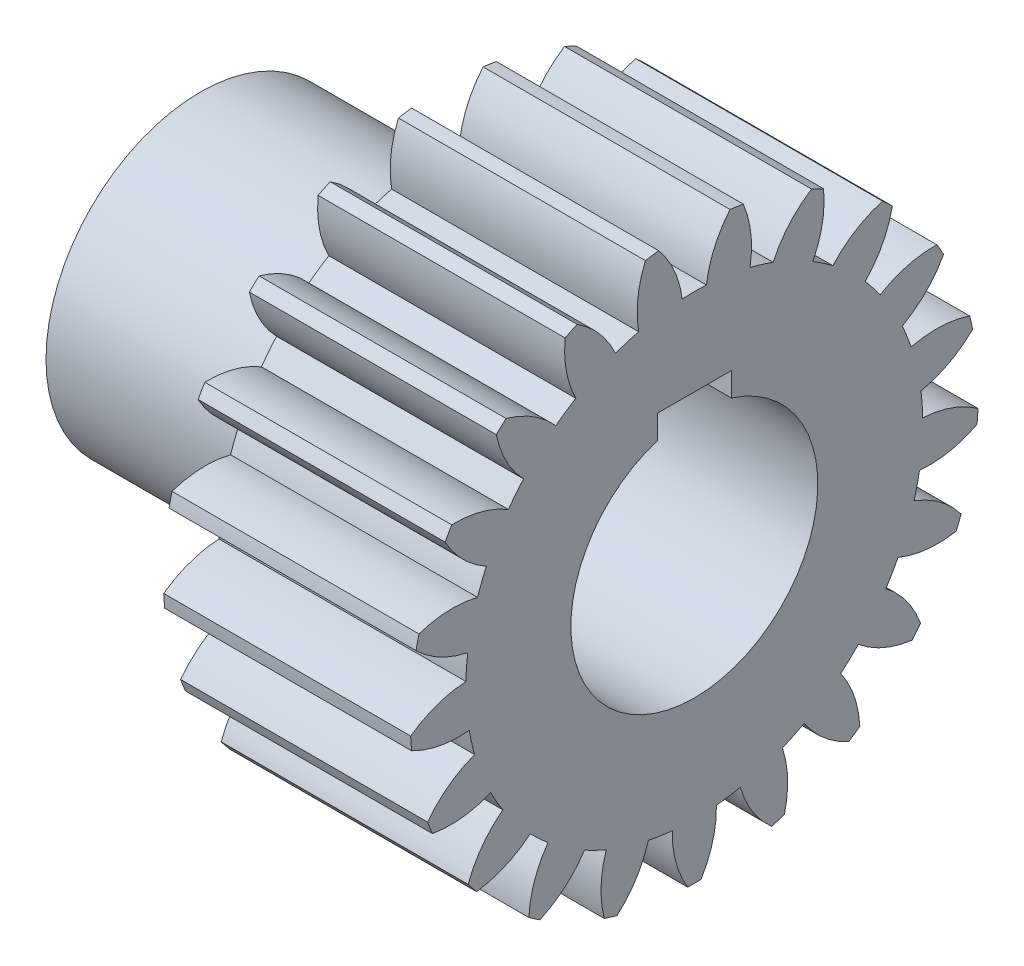
SolidWorks part; units mm, degrees
ref_plane "Plane1" through (0, 0, 0) normal (0, 0, 1) x (1, 0, 0)
ref_plane "Plane2" through (0, 0, 0) normal (0, 1, 0) x (1, 0, 0)
ref_plane "Plane3" through (0, 0, 0) normal (1, 0, 0) x (0, 0, -1)
sketch "HoldingSke" plane through (0, 0, 0) normal (0, 1, 0) x (1, 0, 0)
  line L0 (0, 0) -> (0.1556, -0.0597)
  line L1 (-15, 0) -> (100, 0) construction
  line L2 (0, 0) -> (-2.1039, 2.3779)
  line L3 (0, 0) -> (-11.863, 4.5341)
  line L4 (0, 0) -> (8.0624, 3.0949)
  line L5 (0, 0) -> (-112.4343, -41.9347)
  line L6 (0, 0) -> (-49.7378, -33.5582)
  line L7 (-2.1039, 2.3779) -> (23.726, 119.565)
  line L8 (-76.2, 54.61) -> (-71.8, 54.61)
  line L9 (-71.009, 38.7566) -> (-53.1078, 45.2721)
  line L10 (-76.2, 71.12) -> (104.1128, 71.12)
  line L11 (0, 0) -> (-60, 0)
  line L12 (-76.2, 101.6) -> (-75.993, 101.6)
  line L13 (24.9733, 27.94) -> (52.9518, 28.4284)
  line L14 (24.9733, 27.94) -> (24.9743, 27.94)
  line L15 (24.9733, 27.94) -> (100.4006, 29.5858)
  line L16 (-63.627, -6) -> (-12.827, -6)
  circle A0 centre (0, 0) radius 30
  circle A1 centre (0, 0) radius 37.5
  circle A2 centre (0, 0) radius 37.5
  circle A3 centre (0, 0) radius 30
  dimension "Num_teeth" = 21
  dimension "Pitch" = 0.1667
  dimension "Overall_len" = 120
  dimension "Show_teeth" = 21
  dimension "Thickness" = 60
  dimension "OAL" = 120.0001
  dimension "Ap" = 20
  dimension "H" = 19.05
  dimension "Pitch_radius" = 180.3128
  dimension "Width" = 60
  dimension "Backlash" = 0.207
  dimension "Addendum_fac" = 1
  dimension "Dedendum_fac" = 1.25
  dimension "Clearance_fac" = 0.25
  dimension "Dedendum_add" = 0.001
  dimension "Module" = 6
sketch "BasProSke" plane through (0, 0, 0) normal (0, 1, 0) x (1, 0, 0)
  line L0 (-10, 0) -> (60, 0) construction
  line L1 (0, 0) -> (0, 69)
  line L2 (0, 0) -> (60, 0)
  line L3 (60, 0) -> (60, 69)
  line L4 (60, 69) -> (0, 69)
  dimension "Thickness" = 60
  dimension "Diameter" = 138
revolve "Base-Revolve" add sketch "BasProSke" angle 360 about L0
sketch "TooCutSke" plane through (0, 0, 0) normal (1, 0, 0) x (0, 0, -1)
  line L1 (0, 0) -> (0, 107) construction
  line L2 (0, 0) -> (-5.0701, 62.7957) construction
  line L3 (0, 0) -> (-18.7346, 124.2959) construction
  line L4 (-5.0701, 62.7957) -> (-9.3673, 62.148) construction
  arc A0 (2.9399, 55.4211) -> (-2.9399, 55.4211) centre (0, 0) ccw
  arc A1 (8.6963, 68.4754) -> (-8.6963, 68.4754) centre (0, 0) ccw
  circle A2 centre (0, 0) radius 63 construction
  circle A3 centre (0, 0) radius 59.2006 construction
  arc A4 (-2.9399, 55.4211) -> (-8.6963, 68.4754) centre (-27.9327, 52.1965) ccw
  arc A5 (8.6963, 68.4754) -> (2.9399, 55.4211) centre (27.9327, 52.1965) ccw
  dimension "Root_dia" = 110.998
  dimension "Overcut_dia" = 138.0508
  dimension "Pitch_dia" = 126
  dimension "Base_dia" = 118.4013
  dimension "Flank_rad" = 25.2
  dimension "Half_ang" = 8.571
  dimension "Half_CT" = 4.3457
extrude "ToothCut" cut sketch "TooCutSke" along normal through all
fillet "Breaks" [suppressed] radius 0.12
fillet "RootFillets" [suppressed] radius 1.501
pattern_circular "TeethCuts" count 21 every 17.143 about axis through (-10, 0, 0) along (1, 0, 0) of "ToothCut", "RootFillets", "Breaks"
sketch "HubNeaOneSke" plane through (0, 0, 0) normal (-1, 0, 0) x (0, 0, 1)
  circle A0 centre (0, 0) radius 37.5
extrude "HubNearOne" add sketch "HubNeaOneSke" along normal blind 60.0001
sketch "HubNeaBotSke" plane through (0, 0, 0) normal (-1, 0, 0) x (0, 0, 1)
  circle A0 centre (0, 0) radius 37.5
extrude "HubNearBoth" [suppressed] add sketch "HubNeaBotSke" along normal blind 30
ref_plane "FarPln" through (60, 0, 0) normal (1, 0, 0) x (0, 0, -1)
sketch "HubFarSke" plane through (60, 0, 0) normal (1, 0, 0) x (0, 0, -1)
  circle A0 centre (0, 0) radius 37.5
extrude "HubFar" [suppressed] add sketch "HubFarSke" along normal blind 30
sketch "BorSke" plane through (0, 0, 0) normal (1, 0, 0) x (0, 0, -1)
  circle A0 centre (0, 0) radius 30
extrude "Bore" cut sketch "BorSke" along normal mid plane 240.0001
sketch "KeySke" plane through (0, 0, 0) normal (1, 0, 0) x (0, 0, -1)
  line L0 (-9, 0) -> (-9, 34.4)
  line L1 (-9, 34.4) -> (9, 34.4)
  line L2 (9, 34.4) -> (9, 0)
  line L3 (0, 0) -> (0, 34) construction
  line L4 (-9, 0) -> (9, 0)
extrude "Keyway" cut sketch "KeySke" along normal mid plane 240.0001
pattern_circular "Keyway2" [suppressed] count 2 every 90 about axis through (-10, 0, 0) along (1, 0, 0)
equation "' \"Module@HoldingSke\" = 6.35"
equation "' \"Num_teeth@HoldingSke\" = 12"
equation "' \"Ap@HoldingSke\" =  20"
equation "' \"Ap@HoldingSke\" = 20"
equation "' \"Width@HoldingSke\" = 0.5 * 25.4"
equation "' \"Hub_dia@HoldingSke\"= 1 * 25.4"
equation "' \"Hub_dia@HoldingSke\" = 1 * 25.4"
equation "' \"Overall_len@HoldingSke\" = 1.0 * 25.4"
equation "' \"Bore@HoldingSke\" = 0.75 * 25.4"
equation "' \"T_dim@HoldingSke\" = 0.1 * 25.4"
equation "' \"Width@KeySke\" = 0.25 * 25.4"
equation "' \"Show_teeth@HoldingSke\" = 13"
equation "' \"Backlash@HoldingSke\" = 0.009 * 25.4"
equation "' \"Addendum_fac@HoldingSke\" = 1.0"
equation "' \"Dedendum_fac@HoldingSke\" = 1.25"
equation "' \"Dedendum_add@HoldingSke\" = 0.00005 * 25.4"
equation "' \"Clearance_fac@HoldingSke\" = 0.25"
equation "\"Pitch@HoldingSke\" = 1 / \"Module@HoldingSke\""
equation "\"Overcut_dia@TooCutSke\" = (\"Num_teeth@HoldingSke\" + 2 * \"Addendum_fac@HoldingSke\") / \"Pitch@HoldingSke\" + 0.002 * 25.4"
equation "\"Pitch_dia@TooCutSke\" = \"Num_teeth@HoldingSke\" / \"Pitch@HoldingSke\""
equation "\"Base_dia@TooCutSke\" = \"Num_teeth@HoldingSke\" / \"Pitch@HoldingSke\" * cos((\"Ap@HoldingSke\"  * 3.14159265 / 180))"
equation "\"Root_dia@TooCutSke\" = (\"Num_teeth@HoldingSke\" + 2) / \"Pitch@HoldingSke\" - 2 * (\"Addendum_fac@HoldingSke\" + \"Dedendum_fac@HoldingSke\") / \"Pitch@HoldingSke\" - \"Dedendum_add@HoldingSke\" * 2"
equation "\"Half_ang@TooCutSke\" = 180 / \"Num_teeth@HoldingSke\""
equation "\"Half_CT@TooCutSke\" = \"Num_teeth@HoldingSke\" / \"Pitch@HoldingSke\" * sin((3.14159265 / 2 / \"Num_teeth@HoldingSke\")) / 2 - 7 * \"Backlash@HoldingSke\" / 4"
equation "\"Flank_rad@TooCutSke\" = \"Num_teeth@HoldingSke\" / \"Pitch@HoldingSke\" / 5"
equation "\"Radius@RootFillets\" = \"Clearance_fac@HoldingSke\" / \"Pitch@HoldingSke\" + \"Dedendum_add@HoldingSke\""
equation "\"Break_rad@Breaks\" = 0.02 / \"Pitch@HoldingSke\""
equation "\"Thickness@HoldingSke\" = \"Width@HoldingSke\""
equation "\"OAL@HoldingSke\" = \"Thickness@HoldingSke\""
equation "\"MHD@HoldingSke\" = (\"Num_teeth@HoldingSke\" + 2) / \"Pitch@HoldingSke\" - 2 * (\"Addendum_fac@HoldingSke\" + \"Dedendum_fac@HoldingSke\")  / \"Pitch@HoldingSke\" - \"Dedendum_add@HoldingSke\" * 2"
equation "\"MBD@HoldingSke\" = (\"Num_teeth@HoldingSke\" + 2) / \"Pitch@HoldingSke\" - 2 * (\"Addendum_fac@HoldingSke\" + \"Dedendum_fac@HoldingSke\")  / \"Pitch@HoldingSke\" - \"Dedendum_add@HoldingSke\" * 2 - 0.002 * 25.4"
equation "\"MHD@HoldingSke\" = ((sgn( \"MHD@HoldingSke\" - \"Hub_dia@HoldingSke\" )-1)*( \"MHD@HoldingSke\" - \"Hub_dia@HoldingSke\" ))/-2+ \"Hub_dia@HoldingSke\""
equation "\"MBD@HoldingSke\" = ((sgn( \"MBD@HoldingSke\" - \"Bore@HoldingSke\" )-1)*( \"MBD@HoldingSke\" - \"Bore@HoldingSke\" ))/-2+ \"Bore@HoldingSke\""
equation "\"OAL@HoldingSke\" = ((sgn( \"OAL@HoldingSke\" - \"Overall_len@HoldingSke\" )+1)*( \"OAL@HoldingSke\" - \"Overall_len@HoldingSke\" ))/2 + \"Overall_len@HoldingSke\" + 0.000002 * 25.4"
equation "\"Num_teeth@TeethCuts\" = int( \"Show_teeth@HoldingSke\" ) + 1"
equation "\"Num_teeth@TeethCuts\" = ((sgn( \"Num_teeth@TeethCuts\" - \"Num_teeth@HoldingSke\" )-1)*( \"Num_teeth@TeethCuts\" - \"Num_teeth@HoldingSke\" ))/-2+ \"Num_teeth@HoldingSke\""
equation "\"Num_teeth@TeethCuts\" = ((sgn( \"Num_teeth@TeethCuts\" - 2.0)+1)*( \"Num_teeth@TeethCuts\" - 2.0))/2 +2.0"
equation "\"Angle@TeethCuts\" = 360.0 / \"Num_teeth@HoldingSke\""
equation "\"Diameter@BasProSke\" = (\"Num_teeth@HoldingSke\" + 2 * \"Addendum_fac@HoldingSke\") / \"Pitch@HoldingSke\""
equation "\"Thickness@BasProSke\"  = \"Thickness@HoldingSke\""
equation "' \"Fillet_rad@BasProSke\" =  \"Thickness@HoldingSke\" * 0.05"
equation "' \"Fillet_rad@BasProSke\" = \"Thickness@HoldingSke\" * 0.05"
equation "\"MHD@HoldingSke\" = ((sgn( \"MHD@HoldingSke\" - \"Root_dia@TooCutSke\" )-1)*( \"MHD@HoldingSke\" - \"Root_dia@TooCutSke\" ))/-2+ \"Root_dia@TooCutSke\""
equation "\"Diameter@HubNeaOneSke\" = \"MHD@HoldingSke\""
equation "\"Length@HubNearOne\" = \"OAL@HoldingSke\" - \"Thickness@BasProSke\""
equation "\"Diameter@HubNeaBotSke\" = \"MHD@HoldingSke\""
equation "\"Length@HubNearBoth\" = ( \"OAL@HoldingSke\" - \"Thickness@BasProSke\" ) / 2.0"
equation "\"Thickness@FarPln\" = \"Thickness@BasProSke\""
equation "\"Diameter@HubFarSke\" = \"MHD@HoldingSke\""
equation "\"Length@HubFar\" = ( \"OAL@HoldingSke\" - \"Thickness@BasProSke\" ) / 2.0"
equation "\"Diameter@BorSke\" = \"MBD@HoldingSke\""
equation "\"D1@Bore\" = \"OAL@HoldingSke\" * 2.0"
equation "\"D1@Keyway\" = \"OAL@HoldingSke\" * 2.0"
equation "\"Offset@KeySke\" = \"T_dim@HoldingSke\" + \"MBD@HoldingSke\" / 2.0"
